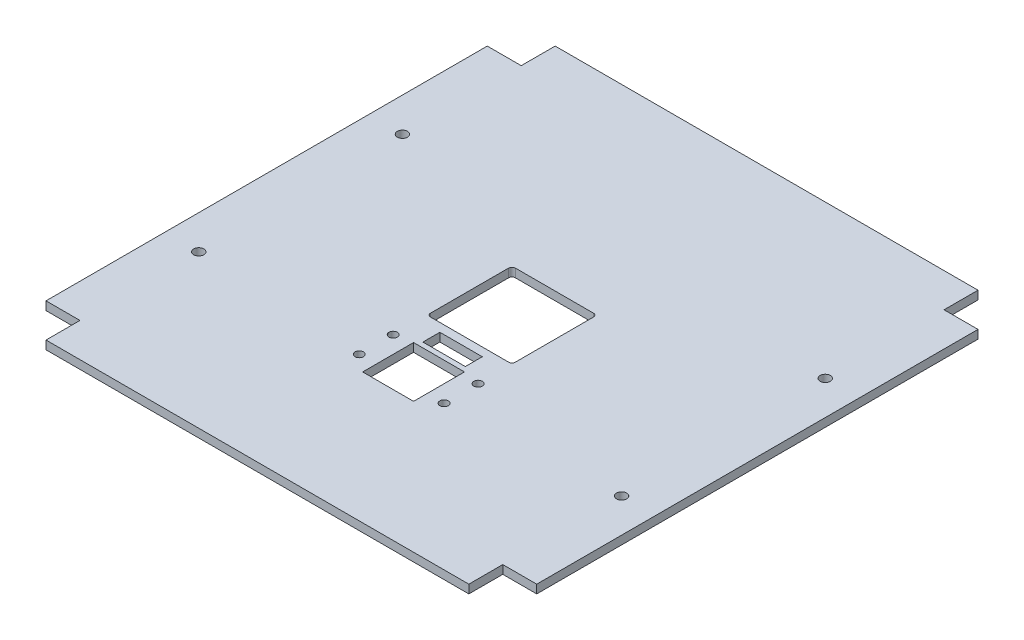
SolidWorks part; units mm, degrees
ref_plane "Plan de face" through (0, 0, 0) normal (0, 0, 1) x (1, 0, 0)
ref_plane "Plan de dessus" through (0, 0, 0) normal (0, 1, 0) x (1, 0, 0)
ref_plane "Plan de droite" through (0, 0, 0) normal (1, 0, 0) x (0, 0, -1)
sketch "Esquisse1" plane through (0, 0, 0) normal (0, 1, 0) x (1, 0, 0)
  line L0 (-174.5839, 0) -> (222.3951, 0) construction
  line L1 (-144.5683, 40) -> (-104.5683, 40)
  line L2 (-104.5683, 40) -> (-104.5683, -40)
  line L3 (-144.5683, -40) -> (-104.5683, -40)
  line L4 (0, 143.2846) -> (0, -128.3979) construction
  line L5 (144.5683, -40) -> (104.5683, -40)
  line L6 (104.5683, 40) -> (104.5683, -40)
  line L7 (144.5683, 40) -> (104.5683, 40)
  line L15 (144.5683, -150) -> (-144.5683, -150)
  line L16 (144.5683, -150) -> (144.5683, 150)
  line L17 (144.5683, 150) -> (-144.5683, 150)
  line L18 (-144.5683, -150) -> (-144.5683, 150)
  line L19 (144.5683, -150) -> (-144.5683, 150) construction
  line L20 (144.5683, 150) -> (-144.5683, -150) construction
  circle A0 centre (0, 0) radius 150
  circle A1 centre (-124.5683, 60) radius 3
  circle A2 centre (-124.5683, -60) radius 3
  circle A3 centre (124.5683, -60) radius 3
  circle A4 centre (124.5683, 60) radius 3
  point P9 (-104.5683, 0)
  dimension "D1" = 300
  dimension "D4" = 6
  dimension "D5" = 6
  dimension "D2" = 40
  dimension "D3" = 40
  dimension "D6" = 20
  dimension "D7" = 20
  dimension "D8" = 20
  dimension "D9" = 20
extrude "Boss.-Extru.1" add sketch "Esquisse1" along normal blind 5 contours A0 L18 L15 | A0 L15 L16 | L5 L16 L7 L6 | L7 A0 L1 L2 L3 L5 L6 A3 A2 A1 A4 | L18 L3 L2 L1 | A0 L17 L18 | A0 L16 L17
sketch "Esquisse2" plane through (0, 5, 0) normal (0, 1, 0) x (1, 0, 0)
  line L1 (23, -25) -> (-23, -25)
  line L2 (25, -23) -> (25, 23)
  line L3 (23, 25) -> (-23, 25)
  line L4 (-25, -23) -> (-25, 23)
  line L5 (25, -25) -> (-25, 25) construction
  line L6 (25, 25) -> (-25, -25) construction
  line L7 (15, -73) -> (-15, -73)
  line L8 (15, -73) -> (15, -43)
  line L9 (15, -43) -> (-15, -43)
  line L10 (-15, -73) -> (-15, -43)
  line L11 (15, -73) -> (-15, -43) construction
  line L12 (15, -43) -> (-15, -73) construction
  line L13 (12.5, -40) -> (-12.5, -40)
  line L14 (12.5, -40) -> (12.5, -30)
  line L15 (12.5, -30) -> (-12.5, -30)
  line L16 (-12.5, -40) -> (-12.5, -30)
  line L17 (12.5, -40) -> (-12.5, -30) construction
  line L18 (12.5, -30) -> (-12.5, -40) construction
  arc A0 (-23, -25) -> (-25, -23) centre (-23, -23) cw
  arc A1 (23, -25) -> (25, -23) centre (23, -23) ccw
  arc A2 (25, 23) -> (23, 25) centre (23, 23) ccw
  arc A3 (-23, 25) -> (-25, 23) centre (-23, 23) ccw
  circle A4 centre (25, -45) radius 2.5
  circle A5 centre (25, -65) radius 2.5
  circle A6 centre (-25, -45) radius 2.5
  circle A7 centre (-25, -65) radius 2.5
  point P0 (0, 0)
  point P18 (0, -58)
  point P31 (0, 0)
  point P32 (0, -34.1138)
  point P33 (-25, -45)
  point P34 (-25, -43)
  point P35 (0, 0)
  point P36 (-25, -45.0797)
  point P37 (0, -35)
  dimension "D3" = 2
  dimension "D7" = 5
  dimension "D8" = 5
  dimension "D9" = 5
  dimension "D10" = 5
  dimension "D1" = 50
  dimension "D2" = 50
  dimension "D4" = 30
  dimension "D5" = 30
  dimension "D6" = 18
  dimension "D11" = 10
  dimension "D12" = 10
  dimension "D13" = 20
  dimension "D14" = 2
  dimension "D15" = 25
  dimension "D16" = 10
  dimension "D17" = 5
extrude "Enlèv. mat.-Extru.1" cut sketch "Esquisse2" against normal through all
sketch "Esquisse4" plane through (0, 5, 0) normal (0, 1, 0) x (1, 0, 0)
  line L0 (-144.5683, 130) -> (-124.5683, 130)
  line L1 (-144.5683, -150) -> (-144.5683, 150) construction
  line L2 (-124.5683, 130) -> (-124.5683, 150)
  line L3 (144.5683, 150) -> (-144.5683, 150) construction
  line L4 (0, 141.9994) -> (0, -109.0539) construction
  line L5 (124.5683, 130) -> (124.5683, 150)
  line L7 (-238.5424, 0) -> (296.0928, 0) construction
  line L8 (144.5683, 130) -> (124.5683, 130)
  line L9 (144.5683, -130) -> (124.5683, -130)
  line L10 (124.5683, -130) -> (124.5683, -150)
  line L11 (-124.5683, -130) -> (-124.5683, -150)
  line L12 (-144.5683, -130) -> (-124.5683, -130)
  line L13 (-144.5683, 130) -> (-144.5683, 150)
  line L14 (-144.5683, 150) -> (-124.5683, 150)
  line L15 (144.5683, 150) -> (124.5683, 150)
  line L16 (144.5683, 130) -> (144.5683, 150)
  line L17 (124.5683, 130) -> (124.5683, 150)
  line L18 (144.5683, 130) -> (124.5683, 130)
  line L19 (144.5683, -130) -> (124.5683, -130)
  line L20 (124.5683, -130) -> (124.5683, -150)
  line L21 (144.5683, -130) -> (144.5683, -150)
  line L22 (144.5683, -150) -> (124.5683, -150)
  line L23 (-144.5683, -150) -> (-124.5683, -150)
  line L24 (-144.5683, -130) -> (-144.5683, -150)
  line L25 (144.5683, -130) -> (124.5683, -130)
  line L26 (124.5683, -130) -> (124.5683, -150)
  line L27 (-124.5683, -130) -> (-124.5683, -150)
  line L28 (-144.5683, -130) -> (-124.5683, -130)
  line M17 (-144.5683, -150) -> (144.5683, -150)
  line M18 (144.5683, -150) -> (144.5683, 150)
  line M19 (144.5683, 150) -> (-144.5683, 150)
  line M20 (-144.5683, 150) -> (-144.5683, -150)
  dimension "D1" = 20
  dimension "D2" = 20
extrude "Enlèv. mat.-Extru.2" cut sketch "Esquisse4" against normal blind 10 contours L0 L2 M19 M20 | L8 L5 M18 M19 | L9 L10 M17 M18 | L12 L11 M20 M17
